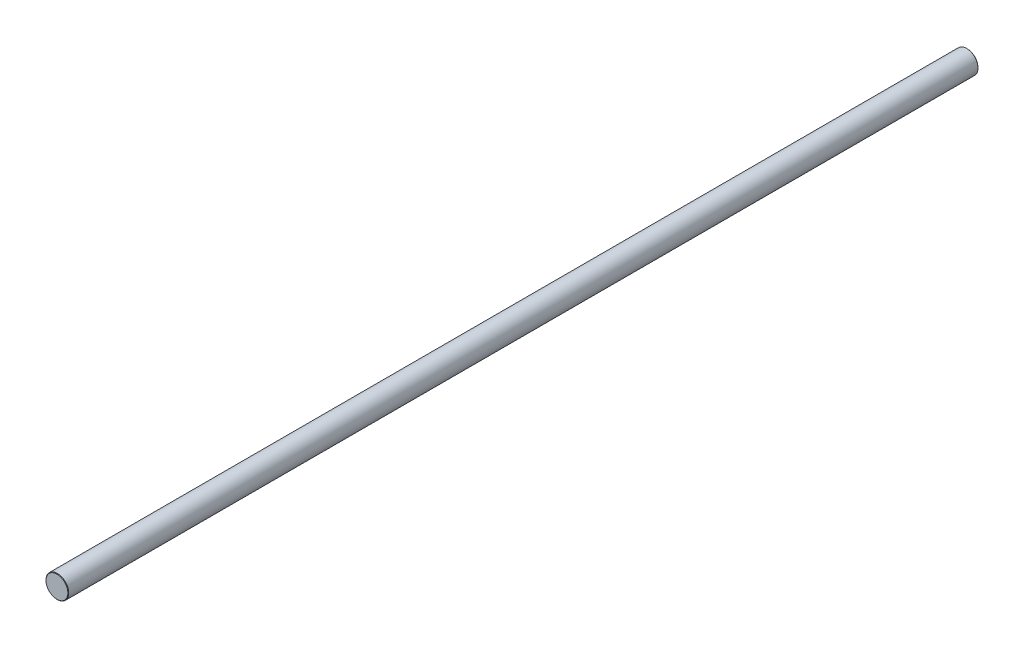
SolidWorks part; units mm, degrees
ref_plane "Front Plane" through (0, 0, 0) normal (0, 0, 1) x (1, 0, 0)
ref_plane "Top Plane" through (0, 0, 0) normal (0, 1, 0) x (1, 0, 0)
ref_plane "Right Plane" through (0, 0, 0) normal (1, 0, 0) x (0, 0, -1)
sketch "Sketch1" plane through (0, 0, 0) normal (0, 0, 1) x (1, 0, 0)
  circle A0 centre (0, 0) radius 5 construction
  dimension "Diameter" = 10
sketch "Sketch2" plane through (0, 0, 0) normal (1, 0, 0) x (0, 0, -1)
  line L0 (200, 0) -> (-200, 0) construction
  point P0 (-160, 0)
  point P3 (0, 0)
  point P4 (160, 0)
  point P6 (-140, 0)
  point P7 (140, 0)
  dimension "Length" = 400
  dimension "D1" = 40
  dimension "D2" = 40
  dimension "D3" = 60
  dimension "D4" = 60
sketch "Sketch3" plane through (0, 0, 0) normal (0, 0, 1) x (1, 0, 0)
  circle A0 centre (0, 0) radius 5 construction
  circle A1 centre (0, 0) radius 5
extrude "Boss-Extrude1" add sketch "Sketch3" along normal up to vertex (200 mm away) and the other way up to vertex (200 mm away) up to point (0, 0, 200) other way up to point (0, 0, -200)
chamfer "Chamfer1" distance 0.2 angle 45 2 edges at (5, 0, 200) (5, 0, -200)
equation "\"D1@Chamfer1\"=\"Diameter@Sketch1\"*.02"
equation "\"D1@Sketch2\"=\"D2@Sketch2\""
equation "\"D2@Sketch2\"=\"Length@Sketch2\"*.1"
equation "\"D3@Sketch2\"=\"Length@Sketch2\"*.15"
equation "\"D4@Sketch2\"=\"D3@Sketch2\""
